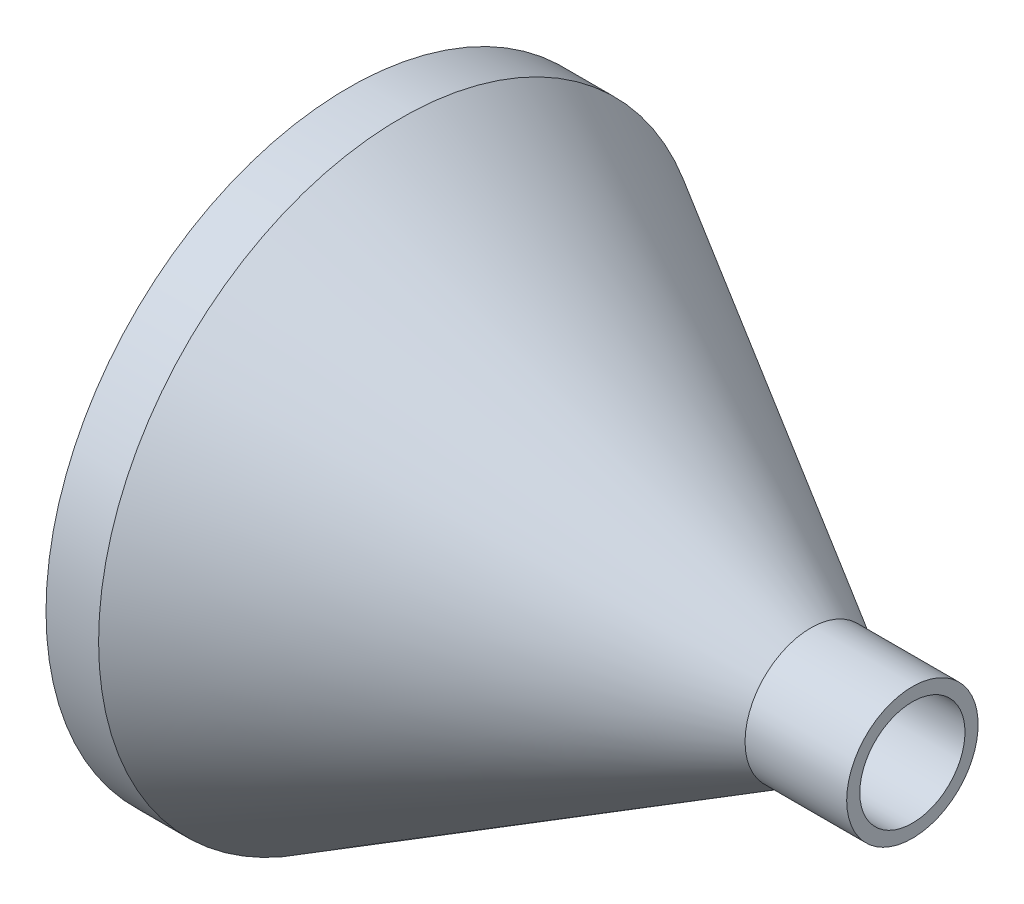
SolidWorks part; units mm, degrees
ref_plane "Front Plane" through (0, 0, 0) normal (0, 0, 1) x (1, 0, 0)
ref_plane "Top Plane" through (0, 0, 0) normal (0, 1, 0) x (1, 0, 0)
ref_plane "Right Plane" through (0, 0, 0) normal (1, 0, 0) x (0, 0, -1)
sketch "Sketch1" plane through (0, 0, 0) normal (0, 0, 1) x (1, 0, 0)
  line L0 (0, 73.025) -> (0, 69.85)
  line L1 (0, 69.85) -> (11.8493, 69.85)
  line L2 (11.8493, 69.85) -> (110.836, 12.7)
  line L3 (110.836, 12.7) -> (136.236, 12.7)
  line L4 (136.236, 12.7) -> (136.236, 15.875)
  line L5 (136.236, 15.875) -> (111.6867, 15.875)
  line L6 (111.6867, 15.875) -> (12.7, 73.025)
  line L7 (12.7, 73.025) -> (0, 73.025)
  line L8 (0, 0) -> (160.4287, 0) construction
  point P8 (160.4287, 0)
  dimension "D1" = 3.175
  dimension "D2" = 3.175
  dimension "D3" = 3.175
  dimension "D4" = 25.4
  dimension "D5" = 30
  dimension "D6" = 25.4
  dimension "D7" = 73.025
  dimension "D8" = 12.7
revolve "Revolve1" add sketch "Sketch1" angle 360 about L8
